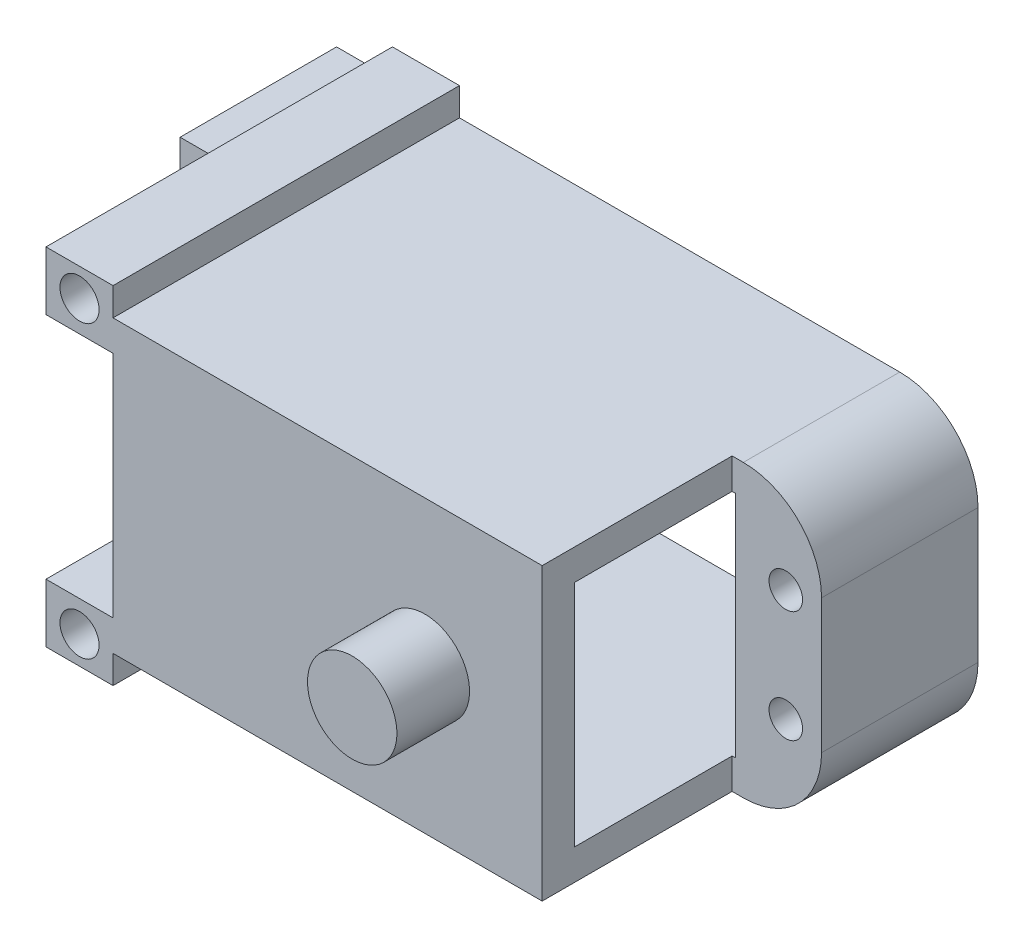
SolidWorks part; units mm, degrees
ref_plane "Спереди" through (0, 0, 0) normal (0, 0, 1) x (1, 0, 0)
ref_plane "Сверху" through (0, 0, 0) normal (0, 1, 0) x (1, 0, 0)
ref_plane "Справа" through (0, 0, 0) normal (1, 0, 0) x (0, 0, -1)
ref_plane "Плоскость4" through (0, 0, 12) normal (0, 0, 1) x (1, 0, 0)
sketch "Эскиз1" plane through (0, 0, 12) normal (0, 0, 1) x (1, 0, 0)
  line L0 (-28.7, 15.5) -> (-28.7, -13)
  line L1 (-28.7, -13) -> (28.7, -13)
  line L2 (28.7, -13) -> (28.7, 15.5)
  line L3 (28.7, 15.5) -> (-28.7, 15.5)
extrude "Бобышка-Вытянуть1" add sketch "Эскиз1" against normal blind 12
sketch "Эскиз2" plane through (0, 0, 12) normal (0, 0, 1) x (1, 0, 0)
  line L0 (28.7, 13) -> (28.7, -13)
  line L1 (28.7, -13) -> (-28.7, -13)
  line L2 (-28.7, -13) -> (-28.7, 13)
  line L3 (-28.7, 13) -> (28.7, 13)
extrude "Бобышка-Вытянуть2" add sketch "Эскиз2" along normal blind 19
sketch "Эскиз3" plane through (-28.7, 0, 0) normal (-1, 0, 0) x (0, 0, 1)
  line L0 (28.1, 10.25) -> (12, 10.25)
  line L1 (12, 10.25) -> (12, -10.25)
  line L2 (12, -10.25) -> (28.1, -10.25)
  line L3 (28.1, -10.25) -> (28.1, 10.25)
extrude "Вырез-Вытянуть1" cut sketch "Эскиз3" against normal blind 7.7
sketch "Эскиз4" plane through (-21, 0, 0) normal (-1, 0, 0) x (0, 0, 1)
  line L0 (0, -10.25) -> (28.1, -10.25)
  line L1 (28.1, -10.25) -> (28.1, 10.25)
  line L2 (28.1, 10.25) -> (0, 10.25)
  line L3 (0, 10.25) -> (0, -10.25)
extrude "Вырез-Вытянуть2" cut sketch "Эскиз4" against normal blind 41.7
sketch "Эскиз5" plane through (20.7, 0, 0) normal (-1, 0, 0) x (0, 0, 1)
  line L0 (0, -10.25) -> (31, -10.25)
  line L1 (31, -10.25) -> (31, 10.25)
  line L2 (31, 10.25) -> (0, 10.25)
  line L3 (0, 10.25) -> (0, -10.25)
extrude "Вырез-Вытянуть3" cut sketch "Эскиз5" against normal blind 0.3
sketch "Эскиз6" plane through (0, 0, 31) normal (0, 0, 1) x (1, 0, 0)
  line L0 (28.7, -13) -> (28.7, 13)
  line L1 (28.7, 13) -> (20.7, 13)
  line L2 (20.7, 13) -> (20.7, 10.25)
  line L3 (20.7, 10.25) -> (21, 10.25)
  line L4 (21, 10.25) -> (21, -10.25)
  line L5 (21, -10.25) -> (20.7, -10.25)
  line L6 (20.7, -10.25) -> (20.7, -13)
  line L7 (20.7, -13) -> (28.7, -13)
extrude "Вырез-Вытянуть4" cut sketch "Эскиз6" against normal blind 2.9
sketch "Эскиз7" plane through (28.7, 0, 0) normal (1, 0, 0) x (0, 0, -1)
  line L0 (-12, 13) -> (0, 13)
  line L1 (0, 13) -> (0, 15.5)
  line L2 (0, 15.5) -> (-12, 15.5)
  line L3 (-12, 15.5) -> (-12, 13)
extrude "Вырез-Вытянуть5" cut sketch "Эскиз7" against normal blind 46.4
sketch "Эскиз8" plane through (-28.7, 0, 0) normal (-1, 0, 0) x (0, 0, 1)
  line L0 (12, -13) -> (31, -13)
  line L1 (31, -13) -> (31, 13)
  line L2 (31, 13) -> (12, 13)
  line L3 (12, 13) -> (12, 10.25)
  line L4 (12, 10.25) -> (28.1, 10.25)
  line L5 (28.1, 10.25) -> (28.1, -10.25)
  line L6 (28.1, -10.25) -> (12, -10.25)
  line L7 (12, -10.25) -> (12, -13)
extrude "Вырез-Вытянуть6" cut sketch "Эскиз8" against normal blind 7.7
sketch "Эскиз9" plane through (0, 0, 28.1) normal (0, 0, 1) x (1, 0, 0)
  line L0 (28.7, -13) -> (28.7, 13)
  line L1 (28.7, 13) -> (20.7, 13)
  line L2 (20.7, 13) -> (20.7, 10.25)
  line L3 (20.7, 10.25) -> (21, 10.25)
  line L4 (21, 10.25) -> (21, -10.25)
  line L5 (21, -10.25) -> (20.7, -10.25)
  line L6 (20.7, -10.25) -> (20.7, -13)
  line L7 (20.7, -13) -> (28.7, -13)
extrude "Вырез-Вытянуть7" cut sketch "Эскиз9" against normal blind 14.1
sketch "Эскиз10" plane through (-21, 0, 0) normal (-1, 0, 0) x (0, 0, 1)
  line L0 (12, -13) -> (31, -13)
  line L1 (31, -13) -> (31, 13)
  line L2 (31, 13) -> (12, 13)
  line L3 (12, 13) -> (12, 10.25)
  line L4 (12, 10.25) -> (28.1, 10.25)
  line L5 (28.1, 10.25) -> (28.1, -10.25)
  line L6 (28.1, -10.25) -> (12, -10.25)
  line L7 (12, -10.25) -> (12, -13)
extrude "Вырез-Вытянуть8" cut sketch "Эскиз10" against normal blind 3.3
sketch "Эскиз11" plane through (0, -13, 0) normal (0, -1, 0) x (1, 0, 0)
  line L0 (-17.7, 0) -> (-28.7, 0)
  line L1 (-28.7, 0) -> (-28.7, 12)
  line L2 (-28.7, 12) -> (-17.7, 12)
  line L3 (-17.7, 12) -> (-17.7, 0)
extrude "Бобышка-Вытянуть3" add sketch "Эскиз11" along normal blind 2.5
sketch "Эскиз12" plane through (-17.7, 0, 0) normal (-1, 0, 0) x (0, 0, 1)
  line L0 (19, -13) -> (19, -10.25)
  line L1 (19, -10.25) -> (31, -10.25)
  line L2 (31, -10.25) -> (31, -13)
  line L3 (31, -13) -> (19, -13)
extrude "Бобышка-Вытянуть4" add sketch "Эскиз12" along normal blind 6
sketch "Эскиз13" plane through (0, -13, 0) normal (0, -1, 0) x (1, 0, 0)
  line L0 (-23.7, 31) -> (-17.7, 31)
  line L1 (-17.7, 31) -> (-17.7, 19)
  line L2 (-17.7, 19) -> (-23.7, 19)
  line L3 (-23.7, 19) -> (-23.7, 31)
extrude "Бобышка-Вытянуть5" add sketch "Эскиз13" along normal blind 2.5
sketch "Эскиз14" plane through (-17.7, 0, 0) normal (-1, 0, 0) x (0, 0, 1)
  line L0 (31, 15.5) -> (31, 10.25)
  line L1 (31, 10.25) -> (19, 10.25)
  line L2 (19, 10.25) -> (19, 15.5)
  line L3 (19, 15.5) -> (31, 15.5)
extrude "Бобышка-Вытянуть6" add sketch "Эскиз14" along normal blind 6
sketch "Эскиз15" plane through (0, 0, 0) normal (0, 0, -1) x (-1, 0, 0)
  line L0 (28.7, -15.5) -> (28.7, -13)
  line L1 (28.7, -13) -> (23.7, -13)
  line L2 (23.7, -13) -> (23.7, -15.5)
  line L3 (23.7, -15.5) -> (28.7, -15.5)
extrude "Вырез-Вытянуть9" cut sketch "Эскиз15" against normal through all
sketch "Эскиз16" plane through (0, 0, 0) normal (0, 0, -1) x (-1, 0, 0)
  line L0 (23.7, 15.5) -> (23.7, 13)
  line L1 (23.7, 13) -> (28.7, 13)
  line L2 (28.7, 13) -> (28.7, 15.5)
  line L3 (28.7, 15.5) -> (23.7, 15.5)
extrude "Вырез-Вытянуть10" cut sketch "Эскиз16" against normal through all
sketch "Эскиз17" plane through (0, 0, 12) normal (0, 0, 1) x (1, 0, 0)
  line L0 (-23.7, 13) -> (-23.7, -13)
  line L1 (-23.7, -13) -> (-28.7, -13)
  line L2 (-28.7, -13) -> (-28.7, 13)
  line L3 (-28.7, 13) -> (-23.7, 13)
extrude "Бобышка-Вытянуть7" add sketch "Эскиз17" along normal blind 2
sketch "Эскиз18" plane through (-28.7, 0, 0) normal (-1, 0, 0) x (0, 0, 1)
  line L0 (0, -3) -> (0, 3)
  line L1 (0, 3) -> (10, 3)
  line L2 (10, 3) -> (10, -3)
  line L3 (10, -3) -> (0, -3)
extrude "Бобышка-Вытянуть8" add sketch "Эскиз18" along normal blind 7
ref_plane "Плоскость5" through (0, 0, 0) normal (0, -1, 0) x (1, 0, 0)
sketch "Эскиз19" plane through (0, 0, 0) normal (0, -1, 0) x (1, 0, 0)
  line L0 (14.2, 37.5) -> (10.2, 37.5)
  line L1 (10.2, 37.5) -> (10.2, 31)
  line L2 (10.2, 31) -> (14.2, 31)
  line L3 (14.2, 31) -> (14.2, 37.5)
  line L4 (10.2, 37.5) -> (10.2, 31) construction
revolve "Повернуть1" add sketch "Эскиз19" angle 360 about L4
hole_wizard "Диаметр отверстия Ø3.5 (3.5)1" positions "Эскиз21" profile "Эскиз20" hole size "Ø3.5" standard "Ansi Metric"
sketch "Эскиз21" plane through (0, 0, 31) normal (0, 0, 1) x (1, 0, 0)
  point P0 (-20.7, 13)
  point P1 (-20.7, -13)
sketch "Эскиз20" plane through (-20.7, 13, 31) normal (1, 0, 0) x (0, -1, 0)
  line L0 (0, 0) -> (0, 12)
  line L1 (0, 12) -> (1.75, 12)
  line L2 (1.75, 12) -> (1.75, 0)
  line L5 (1.75, 0) -> (0, 0)
  line L11 (0, -6.35) -> (0, 107.95) construction
  dimension "Диаметр сквозного отверстия" = 3.5
  dimension "Глубина сквозного отверстия" = 12
hole_wizard "Диаметр отверстия Ø3.5 (3.5)2" positions "Эскиз23" profile "Эскиз22" hole size "Ø3.5" standard "Ansi Metric" end condition through all
sketch "Эскиз23" plane through (0, 0, 0) normal (0, 0, -1) x (-1, 0, 0)
  point P0 (32.7, 0)
sketch "Эскиз22" plane through (-32.7, 0, 0) normal (1, 0, 0) x (0, 1, 0)
  line L0 (0, 0) -> (0, 37.5)
  line L1 (0, 37.5) -> (1.75, 37.5)
  line L2 (1.75, 37.5) -> (1.75, 0)
  line L5 (1.75, 0) -> (0, 0)
  line L11 (0, -6.35) -> (0, 107.95) construction
  dimension "Диаметр сквозного отверстия" = 3.5
  dimension "Глубина сквозного отверстия" = 37.5
hole_wizard "Диаметр отверстия Ø3.0 (3)3" positions "Эскиз25" profile "Эскиз24" hole size "Ø3.0" standard "Ansi Metric"
sketch "Эскиз25" plane through (0, 0, 0) normal (0, 0, -1) x (-1, 0, 0)
  point P0 (-25.5, -5)
  point P1 (-25.5, 5)
  point P2 (25.5, -5)
  point P3 (25.5, 5)
sketch "Эскиз24" plane through (25.5, -5, 0) normal (1, 0, 0) x (0, 1, 0)
  line L0 (0, 0) -> (0, 37.5)
  line L1 (0, 37.5) -> (1.5, 37.5)
  line L2 (1.5, 37.5) -> (1.5, 0)
  line L5 (1.5, 0) -> (0, 0)
  line L11 (0, -6.35) -> (0, 107.95) construction
  dimension "Диаметр сквозного отверстия" = 3
  dimension "Глубина сквозного отверстия" = 37.5
hole_wizard "Диаметр отверстия Ø3.5 (3.5)3" positions "Эскиз27" profile "Эскиз26" hole size "Ø3.5" standard "Ansi Metric" end condition through all
sketch "Эскиз27" plane through (0, 0, 12) normal (0, 0, 1) x (1, 0, 0)
  point P0 (-20.7, 13)
  point P1 (-20.7, -13)
sketch "Эскиз26" plane through (-20.7, 13, 12) normal (1, 0, 0) x (0, -1, 0)
  line L0 (0, 0) -> (0, 12)
  line L1 (0, 12) -> (1.75, 12)
  line L2 (1.75, 12) -> (1.75, 0)
  line L5 (1.75, 0) -> (0, 0)
  line L11 (0, -6.35) -> (0, 107.95) construction
  dimension "Диаметр сквозного отверстия" = 3.5
  dimension "Глубина сквозного отверстия" = 12
fillet "Скругление1" radius 7 2 edges at (28.7, -13, 7) (28.7, 13, 7)
sketch "Эскиз28" plane through (0, 0, 31) normal (0, 0, 1) x (1, 0, 0)
  line L0 (-28.7, 0) -> (-17.7, 0) construction
  line L1 (-23.7, 15.5) -> (-17.7, 15.5)
  line L2 (-23.7, 15.5) -> (-23.7, 10.25)
  line L3 (-23.7, 10.25) -> (-17.7, 10.25)
  line L4 (-17.7, 15.5) -> (-17.7, 10.25)
  line L5 (-28.7, -3) -> (-28.7, 3) construction
  line L6 (-17.7, -10.25) -> (-17.7, 10.25) construction
  line L7 (-23.7, -10.25) -> (-17.7, -10.25)
  line L8 (-17.7, -15.5) -> (-17.7, -10.25)
  line L9 (-23.7, -15.5) -> (-17.7, -15.5)
  line L10 (-23.7, -15.5) -> (-23.7, -10.25)
  circle A0 centre (-20.7, 13) radius 1.75
  circle A1 centre (-20.7, -13) radius 1.75
extrude "Бобышка-Вытянуть9" add sketch "Эскиз28" against normal up to surface (7 mm away) from surface at -12 up to face at (-18.95, 13, 12) starting at face at (-18.95, 13, 19)
